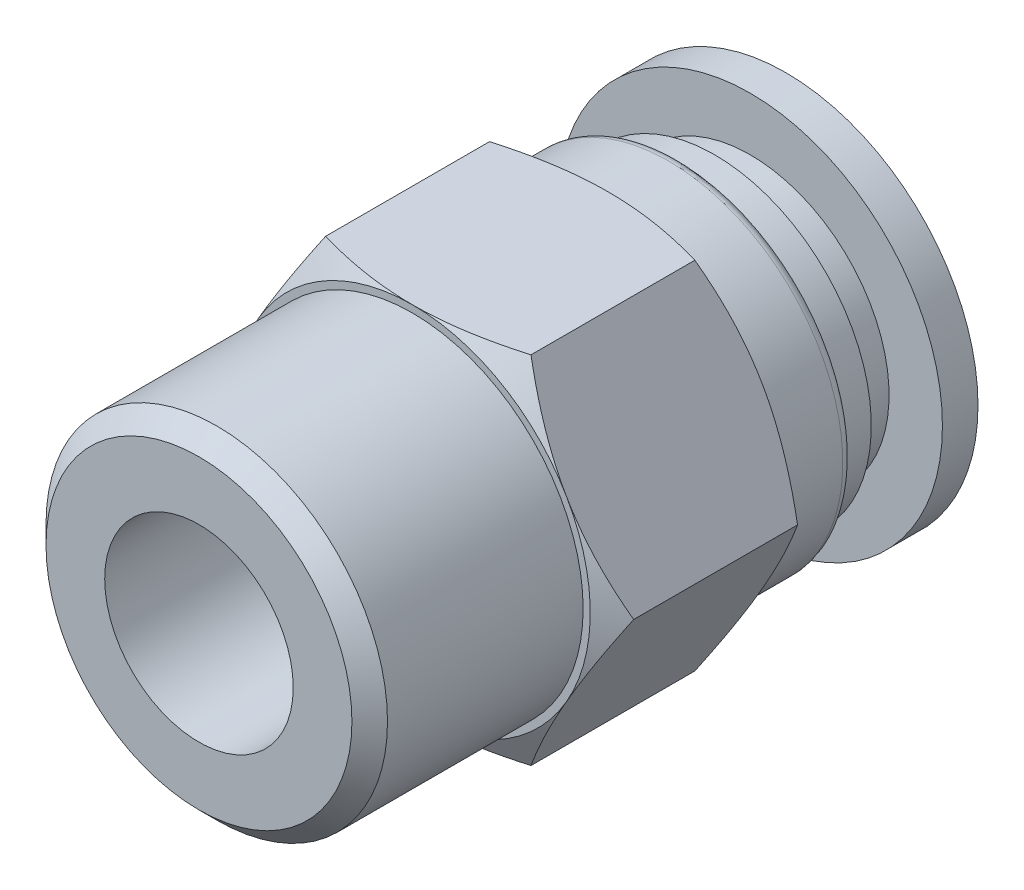
SolidWorks part; units mm, degrees
material "Latón de alto plomo, UNS C34200"
ref_plane "Alzado" through (0, 0, 0) normal (0, 0, 1) x (1, 0, 0)
ref_plane "Planta" through (0, 0, 0) normal (0, 1, 0) x (1, 0, 0)
ref_plane "Vista lateral" through (0, 0, 0) normal (1, 0, 0) x (0, 0, -1)
ref_plane "Plano1" through (0, 0, 0) normal (0, 0, -1) x (-1, 0, 0)
sketch "Croquis1" plane through (0, 0, 0) normal (0, 0, -1) x (-1, 0, 0)
  line L0 (5.7735, 0) -> (2.8868, 5)
  line L1 (2.8868, 5) -> (-2.8868, 5)
  line L2 (-2.8868, 5) -> (-5.7735, 0)
  line L3 (-5.7735, 0) -> (-2.8868, -5)
  line L4 (-2.8868, -5) -> (2.8868, -5)
  line L5 (2.8868, -5) -> (5.7735, 0)
extrude "Saliente-Extruir1" add sketch "Croquis1" against normal blind 5.5
ref_plane "Plano2" through (0, 0, 0) normal (0, -1, 0) x (1, 0, 0)
sketch "Croquis2" plane through (0, 0, 0) normal (0, -1, 0) x (1, 0, 0)
  line L0 (4.3, 11.5) -> (0, 11.5)
  line L1 (0, 11.5) -> (0, 5.5)
  line L2 (0, 5.5) -> (4.8, 5.5)
  line L3 (4.8, 5.5) -> (4.8, 11)
  line L4 (4.8, 11) -> (4.3, 11.5)
  line L5 (0, 11.5) -> (0, 5.5) construction
revolve "Revolución1" add sketch "Croquis2" angle 360 about L5
sketch "Croquis3" plane through (0, 0, 0) normal (0, -1, 0) x (1, 0, 0)
  line L0 (4.9, 0) -> (0, 0)
  line L1 (0, 0) -> (0, -5)
  line L2 (0, -5) -> (5.4, -5)
  line L3 (5.4, -5) -> (5.4, -4)
  line L4 (5.4, -4) -> (3.9, -4)
  line L5 (3.9, -4) -> (3.9, -3)
  line L6 (3.9, -3) -> (4.4, -3)
  line L7 (4.4, -3) -> (4.4, -2)
  line L8 (4.4, -2) -> (4.6, -2)
  line L9 (4.9, -1.7) -> (4.9, 0)
  line L10 (0, 0) -> (0, -5) construction
  arc A0 (4.6, -2) -> (4.9, -1.7) centre (4.6, -1.7) ccw
revolve "Revolución2" add sketch "Croquis3" angle 360 about L10
hole_wizard "Refrentado para perno con cabeza hexagonal de M51" positions "Croquis5" profile "Croquis4" counterbore size "M5" standard "Ansi Metric"
sketch "Croquis5" plane through (0, 0, -5) normal (0, 0, -1) x (-1, 0, 0)
  point P0 (0, 0)
sketch "Croquis4" plane through (0, 0, -5) normal (1, 0, 0) x (0, 1, 0)
  line L0 (0, 0) -> (0, 16.5)
  line L1 (0, 16.5) -> (2.65, 16.5)
  line L3 (2.65, 16.5) -> (2.65, 6)
  line L4 (2.65, 6) -> (3.4, 6)
  line L5 (3.4, 6) -> (3.4, 0)
  line L7 (3.4, 0) -> (0, 0)
  line L11 (0, -6.35) -> (0, 107.95) construction
  dimension "Diámetro de taladro hasta el siguiente" = 5.3
  dimension "Profundidad de taladro hasta el siguiente" = 16.5
  dimension "Diámetro de refrentado" = 6.8
  dimension "Profundidad de refrentado" = 6
sketch "Croquis9" plane through (0, 0, 0) normal (1, 0, 0) x (0, 0, -1)
  line L0 (-5.5, 5) -> (-5.5, 6.593)
  line L1 (-5.5, 6.593) -> (-4.5803, 6.593)
  line L2 (-4.5803, 6.593) -> (-5.5, 5)
  line L3 (-2.75, 5) -> (-2.75, 8.0576) construction
  line L4 (-0.9197, 6.593) -> (0, 5)
  line L5 (0, 6.593) -> (-0.9197, 6.593)
  line L6 (0, 5) -> (0, 6.593)
  line L7 (0, 0) -> (-15.3681, 0) construction
revolve "Cortar-Revolución1" cut sketch "Croquis9" angle 360 about L7
